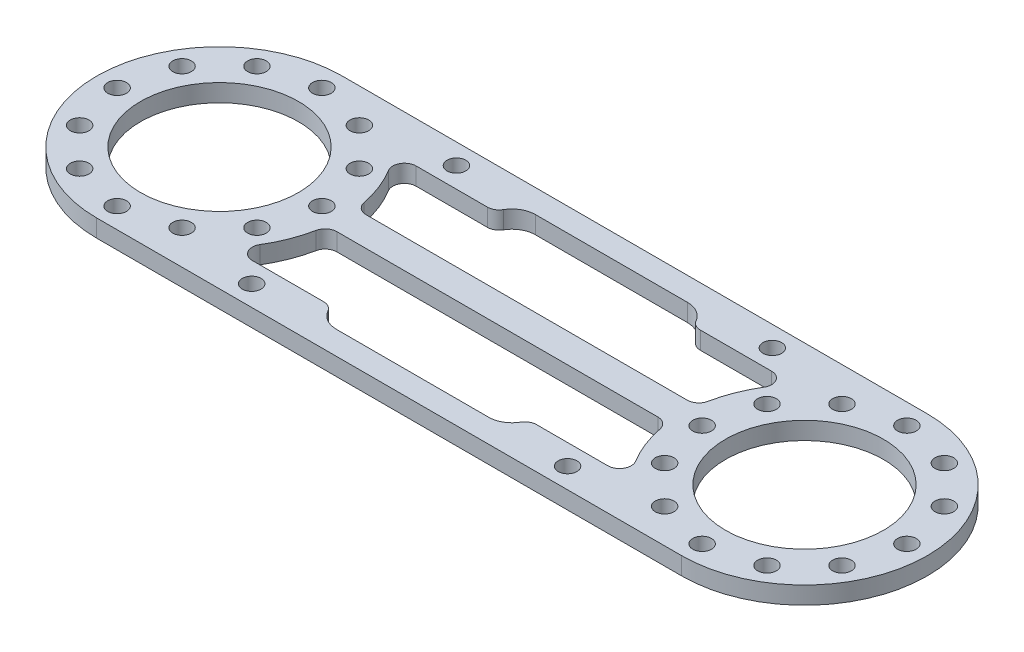
SolidWorks part; units mm, degrees
material "Thornel Mat VMA"
ref_plane "前视基准面" through (0, 0, 0) normal (0, 0, 1) x (1, 0, 0)
ref_plane "上视基准面" through (0, 0, 0) normal (0, 1, 0) x (1, 0, 0)
ref_plane "右视基准面" through (0, 0, 0) normal (1, 0, 0) x (0, 0, -1)
other "Configuration Table"
sketch "草图1" plane through (0, 0, 0) normal (0, 1, 0) x (1, 0, 0)
  line L0 (-50, 0) -> (50, 0) construction
  line L1 (-50, 21) -> (50, 21)
  line L2 (-50, -21) -> (50, -21)
  line L3 (0, -32.5) -> (0, 32.763) construction
  line L4 (-87.3644, -32.5) -> (86.7644, -32.5) construction
  arc A0 (-50, 21) -> (-50, -21) centre (-50, 0) ccw
  arc A1 (50, -21) -> (50, 21) centre (50, 0) ccw
  circle A2 centre (-50, 0) radius 13.5
  circle A3 centre (-50, 17.5) radius 1.6
  circle A4 centre (-13, 13) radius 1.6
  circle A5 centre (-13, -13) radius 1.6
  circle A6 centre (-41.25, 15.1554) radius 1.6
  circle A7 centre (-34.8446, 8.75) radius 1.6
  circle A8 centre (-32.5, 0) radius 1.6
  circle A9 centre (-34.8446, -8.75) radius 1.6
  circle A10 centre (-41.25, -15.1554) radius 1.6
  circle A11 centre (-50, -17.5) radius 1.6
  circle A12 centre (-58.75, -15.1554) radius 1.6
  circle A13 centre (-65.1554, -8.75) radius 1.6
  circle A14 centre (-67.5, 0) radius 1.6
  circle A15 centre (-65.1554, 8.75) radius 1.6
  circle A16 centre (-58.75, 15.1554) radius 1.6
  circle A17 centre (58.75, 15.1554) radius 1.6
  circle A18 centre (65.1554, 8.75) radius 1.6
  circle A19 centre (67.5, 0) radius 1.6
  circle A20 centre (65.1554, -8.75) radius 1.6
  circle A21 centre (58.75, -15.1554) radius 1.6
  circle A22 centre (50, -17.5) radius 1.6
  circle A23 centre (41.25, -15.1554) radius 1.6
  circle A24 centre (34.8446, -8.75) radius 1.6
  circle A25 centre (32.5, 0) radius 1.6
  circle A26 centre (41.25, 15.1554) radius 1.6
  circle A27 centre (13, -13) radius 1.6
  circle A28 centre (13, 13) radius 1.6
  circle A29 centre (50, 17.5) radius 1.6
  circle A30 centre (50, 0) radius 13.5
  circle A31 centre (34.8446, 8.75) radius 1.6
  point P2 (0, 0)
  point P40 (-50, 0)
  point P67 (50, 0)
  dimension "D2" = 21
  dimension "D3" = 27
  dimension "D5" = 3.2
  dimension "D9" = 3.2
  dimension "D1" = 100
  dimension "D4" = 17.5
  dimension "D6" = 26
  dimension "D7" = 13
  dimension "D8" = 13
  dimension "D11" = 32.5
  dimension "D10" = 12
extrude "凸台-拉伸1" add sketch "草图1" along normal blind 3
sketch "草图2" plane through (0, 3, 0) normal (0, 1, 0) x (1, 0, 0)
  line L1 (-50, 14) -> (50, 14)
  line L2 (-50, 14) -> (-50, -14)
  line L3 (-50, -14) -> (50, -14)
  line L4 (50, 14) -> (50, -14)
  line L5 (-50, -21) -> (50, -21) construction
  circle A0 centre (-13, -13) radius 4
  circle A1 centre (13, -13) radius 4
  circle A2 centre (13, 13) radius 4
  circle A3 centre (-13, 13) radius 4
  circle A4 centre (-50, 0) radius 21
  circle A5 centre (50, 0) radius 21
  point P24 (50, 0)
  point P25 (-50, 0)
  circle M9 centre (13, 13) radius 1.6
  circle M21 centre (-13, 13) radius 1.6
  circle M22 centre (-13, -13) radius 1.6
  circle M39 centre (13, -13) radius 1.6
  dimension "D1" = 8
  dimension "D2" = 7
extrude "切除-拉伸1" cut sketch "草图2" against normal blind 10 contours A5 L1 A2 A3 A4 L3 A0 A1 | L3 A0 M22 | L3 A0 M22 | L3 A1 M39 | L3 A1 M39 | L1 A3 M21 | L1 A3 M21 | L1 A2 M9 | L1 A2 M9
sketch "草图3" plane through (0, 3, 0) normal (0, 1, 0) x (1, 0, 0)
  line L0 (-30.9, 0) -> (30.9, 0)
  circle A0 centre (32.5, 0) radius 1.6 construction
  circle A1 centre (-32.5, 0) radius 1.6 construction
extrude "拉伸-薄壁1" add sketch "草图3" against normal blind 3 thin thin type mid plane wall 5
fillet "圆角1" radius 2 16 edges at (29.1493, 1.5, -2.5) (34.3475, 1.5, -14) (16.873, 1.5, -14) (9.127, 1.5, -14) (-9.127, 1.5, -14) (-16.873, 1.5, -14) (-34.3475, 1.5, -14) (-29.1493, 1.5, -2.5) (-34.3475, 1.5, 14) (-16.873, 1.5, 14) (-9.127, 1.5, 14) (9.127, 1.5, 14) (16.873, 1.5, 14) (34.3475, 1.5, 14) (29.1493, 1.5, 2.5) (-29.1493, 1.5, 2.5)
sketch "草图5" plane through (0, 0, 0) normal (0, 1, 0) x (1, 0, 0)
  line L1 (-10, 14.35) -> (10, 14.35) construction
  line L2 (-10, 14.35) -> (-10, -14.35) construction
  line L3 (-10, -14.35) -> (10, -14.35) construction
  line L4 (10, 14.35) -> (10, -14.35) construction
  line L5 (-10, 14.35) -> (10, -14.35) construction
  line L6 (-10, -14.35) -> (10, 14.35) construction
  point P0 (0, 0)
  dimension "D1" = 20
  dimension "D2" = 28.7
sketch "草图6" plane through (0, 3, 0) normal (0, 1, 0) x (1, 0, 0)
  line L1 (13, -17) -> (-13, -17)
  line L2 (13, -17) -> (13, -12)
  line L3 (13, -12) -> (-13, -12)
  line L4 (-13, -17) -> (-13, -12)
  line L5 (13, 17) -> (-13, 17)
  line L6 (13, 17) -> (13, 12)
  line L7 (13, 12) -> (-13, 12)
  line L8 (-13, 17) -> (-13, 12)
  arc A0 (9.5359, -15) -> (16.4641, -15) centre (13, -13) ccw construction
  arc A1 (16.4641, 15) -> (9.5359, 15) centre (13, 13) ccw construction
  arc A2 (-16.4641, -15) -> (-9.5359, -15) centre (-13, -13) ccw construction
  arc A3 (-16.4641, -15) -> (-9.5359, -15) centre (-13, -13) ccw construction
  point P18 (-13, -17)
  dimension "D1" = 5
extrude "切除-拉伸2" cut sketch "草图6" against normal blind 10
sketch "草图7" plane through (0, 3, 0) normal (0, 1, 0) x (1, 0, 0)
  line L1 (-27, 17.5) -> (27, 17.5) construction
  line L2 (-27, 17.5) -> (-27, -17.5) construction
  line L3 (-27, -17.5) -> (27, -17.5) construction
  line L4 (27, 17.5) -> (27, -17.5) construction
  line L5 (-27, 17.5) -> (27, -17.5) construction
  line L6 (-27, -17.5) -> (27, 17.5) construction
  circle A0 centre (50, 17.5) radius 1.6 construction
  circle A1 centre (32.5, 0) radius 1.6 construction
  circle A2 centre (50, -17.5) radius 1.6 construction
  circle A3 centre (50, 17.5) radius 1.6 construction
  circle A4 centre (32.5, 0) radius 1.6 construction
  circle A5 centre (50, -17.5) radius 1.6 construction
  circle A6 centre (27, -17.5) radius 1.6
  circle A7 centre (27, 17.5) radius 1.6
  circle A8 centre (-27, 17.5) radius 1.6
  circle A9 centre (-27, -17.5) radius 1.6
  point P0 (0, 0)
  dimension "D1" = 54
extrude "切除-拉伸3" cut sketch "草图7" against normal blind 10
